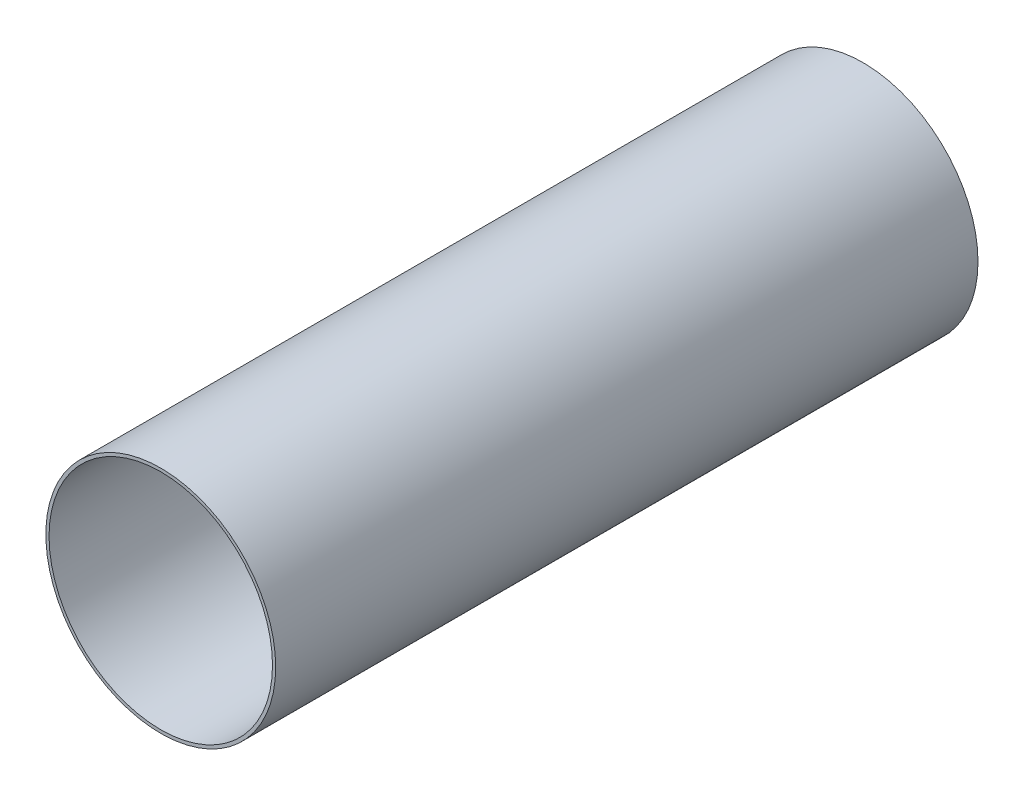
SolidWorks part; units mm, degrees
ref_plane "Front Plane" through (0, 0, 0) normal (0, 0, 1) x (1, 0, 0)
ref_plane "Top Plane" through (0, 0, 0) normal (0, 1, 0) x (1, 0, 0)
ref_plane "Right Plane" through (0, 0, 0) normal (1, 0, 0) x (0, 0, -1)
sketch "Sketch1" plane through (0, 0, 0) normal (0, 0, 1) x (1, 0, 0)
  circle A0 centre (0, 0) radius 36
  circle A1 centre (0, 0) radius 35
  dimension "D1" = 72
  dimension "D2" = 70
extrude "Boss-Extrude1" add sketch "Sketch1" along normal blind 220
